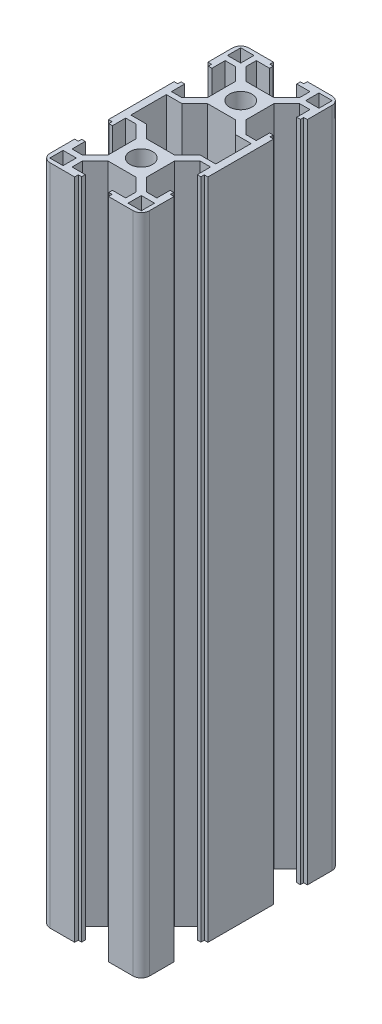
SolidWorks part; units mm, degrees
ref_plane "Front Plane" through (0, 0, 0) normal (0, 0, 1) x (1, 0, 0)
ref_plane "Top Plane" through (0, 0, 0) normal (0, 1, 0) x (1, 0, 0)
ref_plane "Right Plane" through (0, 0, 0) normal (1, 0, 0) x (0, 0, -1)
sketch "Sketch1" plane through (0, 0, 0) normal (0, 1, 0) x (1, 0, 0)
  line L0 (0, 0) -> (0, 15) construction
  line L6 (0, 15) -> (0, 37.9836) construction
  line L7 (0, 15) -> (33.3125, 15) construction
  line L19 (0, 15) -> (27.8511, 42.8511) construction
  line L20 (-4.2444, 20.8) -> (4.2444, 20.8)
  line L21 (5.8, 10.7556) -> (5.8, 19.2444)
  line L22 (8.1, 24.6556) -> (8.1, 27.8)
  line L23 (8.1, 27.8) -> (4.1, 27.8)
  line L24 (4.1, 27.8) -> (4.1, 28.9)
  line L25 (4.1, 28.9) -> (5.1, 28.9)
  line L26 (5.1, 28.9) -> (5.1, 30)
  line L27 (5.1, 30) -> (13.4444, 30)
  line L28 (13.4444, 30) -> (15, 30)
  line L29 (15, 28.4444) -> (15, 30)
  line L30 (9.8, 24.8) -> (13.8, 24.8)
  line L31 (9.8, 24.8) -> (9.8, 28.8)
  line L32 (9.8, 28.8) -> (13.8, 28.8)
  line L33 (13.8, 24.8) -> (13.8, 28.8)
  line L34 (9.8, 24.8) -> (13.8, 28.8) construction
  line L35 (9.8, 28.8) -> (13.8, 24.8) construction
  line L36 (15, 20.1) -> (15, 28.4444)
  line L37 (4.2444, 20.8) -> (8.1, 24.6556)
  line L38 (5.8, 19.2444) -> (9.6556, 23.1)
  line L39 (13.9, 20.1) -> (15, 20.1)
  line L40 (13.9, 19.1) -> (13.9, 20.1)
  line L41 (12.8, 19.1) -> (13.9, 19.1)
  line L42 (12.8, 23.1) -> (12.8, 19.1)
  line L43 (9.6556, 23.1) -> (12.8, 23.1)
  line L44 (8.1, 5.3444) -> (12.8, 5.3444)
  line L46 (9.6556, 6.9) -> (12.8, 6.9)
  line L47 (12.8, 6.9) -> (12.8, 10.9)
  line L48 (12.8, 10.9) -> (13.9, 10.9)
  line L49 (13.9, 10.9) -> (13.9, 9.9)
  line L50 (13.9, 9.9) -> (15, 9.9)
  line L51 (5.8, 10.7556) -> (9.6556, 6.9)
  line L52 (4.2444, 9.2) -> (8.1, 5.3444)
  line L53 (15, 9.9) -> (15, 1.5556)
  line L58 (15, 1.5556) -> (15, 0)
  line L59 (13.4444, 0) -> (15, 0)
  line L60 (12.8, 0) -> (13.4444, 0)
  line L66 (-4.2444, 9.2) -> (4.2444, 9.2)
  line L67 (12.8, 5.3444) -> (12.8, 0)
  line L68 (-12.8, 5.3444) -> (-12.8, 0)
  line L69 (-9.8, 28.8) -> (-13.8, 24.8) construction
  line L70 (-9.8, 24.8) -> (-13.8, 28.8) construction
  line L76 (-12.8, 0) -> (-13.4444, 0)
  line L77 (-13.4444, 0) -> (-15, 0)
  line L78 (-15, 1.5556) -> (-15, 0)
  line L83 (-15, 9.9) -> (-15, 1.5556)
  line L84 (-4.2444, 9.2) -> (-8.1, 5.3444)
  line L85 (-5.8, 10.7556) -> (-9.6556, 6.9)
  line L86 (-13.9, 9.9) -> (-15, 9.9)
  line L87 (-13.9, 10.9) -> (-13.9, 9.9)
  line L88 (-12.8, 10.9) -> (-13.9, 10.9)
  line L89 (-12.8, 6.9) -> (-12.8, 10.9)
  line L90 (-9.6556, 6.9) -> (-12.8, 6.9)
  line L91 (-9.6556, 23.1) -> (-12.8, 23.1)
  line L92 (-12.8, 23.1) -> (-12.8, 19.1)
  line L93 (-12.8, 19.1) -> (-13.9, 19.1)
  line L94 (-13.9, 19.1) -> (-13.9, 20.1)
  line L95 (-13.9, 20.1) -> (-15, 20.1)
  line L96 (-5.8, 19.2444) -> (-9.6556, 23.1)
  line L97 (-4.2444, 20.8) -> (-8.1, 24.6556)
  line L98 (-15, 20.1) -> (-15, 28.4444)
  line L99 (-13.8, 24.8) -> (-13.8, 28.8)
  line L100 (-9.8, 28.8) -> (-13.8, 28.8)
  line L101 (-9.8, 24.8) -> (-9.8, 28.8)
  line L102 (-9.8, 24.8) -> (-13.8, 24.8)
  line L103 (-15, 28.4444) -> (-15, 30)
  line L104 (-13.4444, 30) -> (-15, 30)
  line L105 (-5.1, 30) -> (-13.4444, 30)
  line L106 (-5.1, 28.9) -> (-5.1, 30)
  line L107 (-4.1, 28.9) -> (-5.1, 28.9)
  line L108 (-4.1, 27.8) -> (-4.1, 28.9)
  line L109 (-8.1, 27.8) -> (-4.1, 27.8)
  line L110 (-8.1, 24.6556) -> (-8.1, 27.8)
  line L111 (-5.8, 10.7556) -> (-5.8, 19.2444)
  line L112 (-8.1, 5.3444) -> (-12.8, 5.3444)
  circle A1 centre (0, 15) radius 3.4
  point P2 (-5.8, 15)
  point P13 (11.8, 26.8)
  point P51 (5.8, 15)
  point P61 (0, 9.2)
  point P95 (0, 20.8)
  point P96 (-11.8, 26.8)
  dimension "D2" = 6.8
  dimension "D1" = 15
  dimension "D3" = 9.2
  dimension "D7" = 4
  dimension "D8" = 4.1
  dimension "D9" = 5.1
  dimension "D10" = 1.1
  dimension "D11" = 1.1
  dimension "D12" = 15
  dimension "D13" = 4
  dimension "D14" = 1.2
  dimension "D5" = 4
extrude "Boss-Extrude1" add sketch "Sketch1" along normal blind 200
fillet "Fillet1" radius 2.5 2 edges at (-15, 100, -30) (15, 100, -30)
mirror "Mirror1" about plane through (0, 0, 0) normal (0, 0, 1) of "Fillet1", "Boss-Extrude1"
